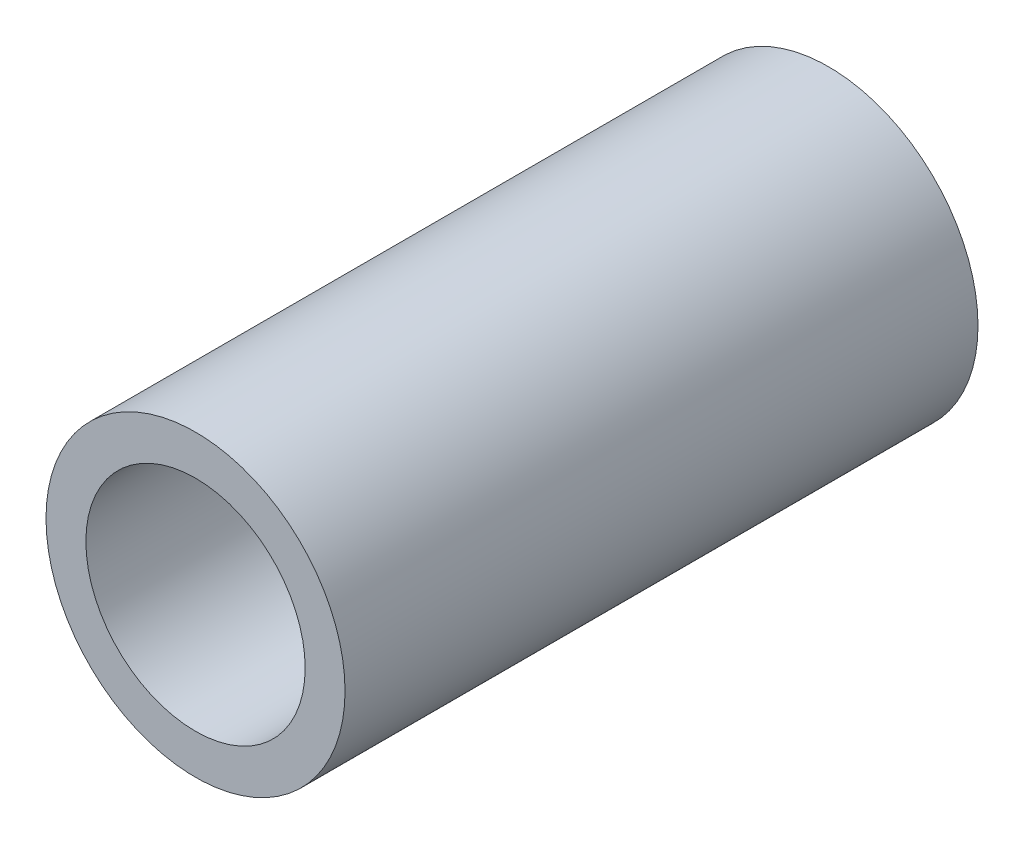
SolidWorks part; units mm, degrees
ref_plane "Front Plane" through (0, 0, 0) normal (0, 0, 1) x (1, 0, 0)
ref_plane "Top Plane" through (0, 0, 0) normal (0, 1, 0) x (1, 0, 0)
ref_plane "Right Plane" through (0, 0, 0) normal (1, 0, 0) x (0, 0, -1)
sketch "Sketch1" plane through (0, 0, 0) normal (0, 0, 1) x (1, 0, 0)
  circle A0 centre (0, 0) radius 1.5
  dimension "D1" = 3
extrude "Boss-Extrude1" add sketch "Sketch1" along normal blind 6.35
sketch "Sketch2" plane through (0, 0, 0) normal (0, 0, -1) x (-1, 0, 0)
  circle A0 centre (0, 0) radius 1.1
  dimension "D1" = 2.2
extrude "Cut-Extrude1" cut sketch "Sketch2" against normal through all
